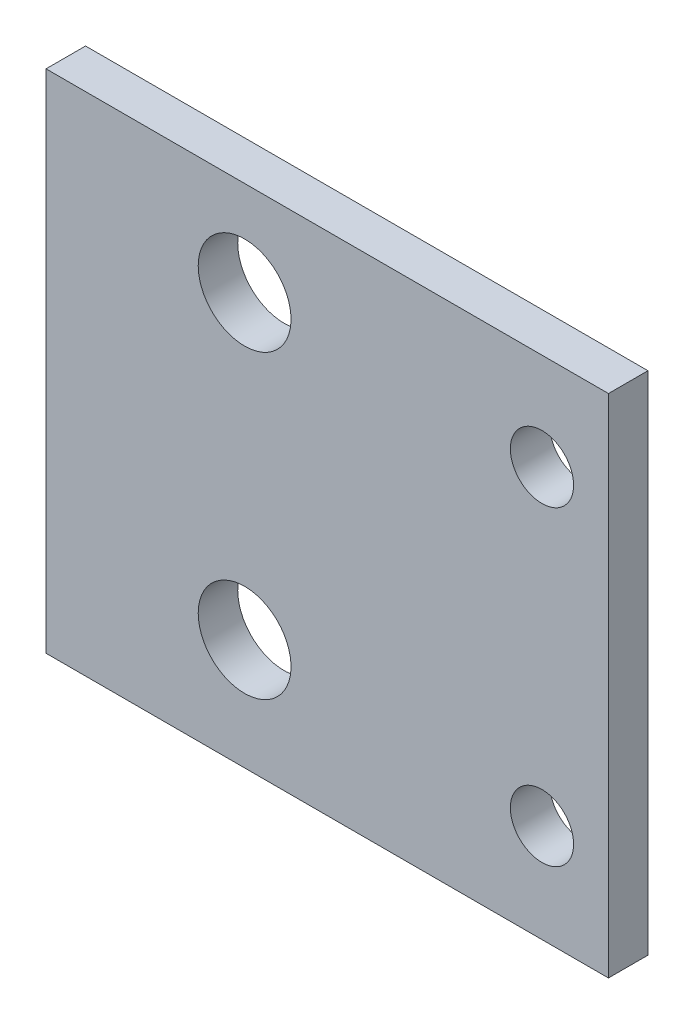
SolidWorks part; units mm, degrees
ref_plane "Front Plane" through (0, 0, 0) normal (0, 0, 1) x (1, 0, 0)
ref_plane "Top Plane" through (0, 0, 0) normal (0, 1, 0) x (1, 0, 0)
ref_plane "Right Plane" through (0, 0, 0) normal (1, 0, 0) x (0, 0, -1)
sketch "Sketch1" plane through (0, 0, 0) normal (0, 0, 1) x (1, 0, 0)
  line L1 (-20, -18) -> (20, -18)
  line L2 (-20, -18) -> (-20, 18)
  line L3 (-20, 18) -> (20, 18)
  line L4 (20, -18) -> (20, 18)
  line L5 (-20, -18) -> (20, 18) construction
  line L6 (-20, 18) -> (20, -18) construction
  point P0 (0, 0)
  dimension "D1" = 36
  dimension "D2" = 40
extrude "Boss-Extrude1" add sketch "Sketch1" along normal blind 2.81
hole_wizard "M4 Clearance Hole1" positions "Sketch3" profile "Sketch2" hole size "M4" standard "ANSI Metric" end condition through all
sketch "Sketch3" plane through (0, 0, 0) normal (0, 0, -1) x (-1, 0, 0)
  point P0 (-15.273, -11)
  point P3 (-15.273, 11.1109)
sketch "Sketch2" plane through (15.273, -11, 0) normal (1, 0, 0) x (0, 1, 0)
  line L0 (0, 0) -> (0, 2.81)
  line L1 (0, 2.81) -> (2.25, 2.81)
  line L2 (2.25, 2.81) -> (2.25, 0)
  line L5 (2.25, 0) -> (0, 0)
  line L11 (0, -6.35) -> (0, 107.95) construction
  dimension "Thru Hole Dia." = 4.5
  dimension "Thru Hole Depth" = 2.81
hole_wizard "M6 Clearance Hole1" positions "Sketch5" profile "Sketch4" hole size "M6" standard "ANSI Metric" end condition through all
sketch "Sketch5" plane through (0, 0, 0) normal (0, 0, -1) x (-1, 0, 0)
  point P0 (5.8771, -10.1116)
  point P2 (5.8771, 11.2827)
sketch "Sketch4" plane through (-5.8771, -10.1116, 0) normal (1, 0, 0) x (0, 1, 0)
  line L0 (0, 0) -> (0, 2.81)
  line L1 (0, 2.81) -> (3.3, 2.81)
  line L2 (3.3, 2.81) -> (3.3, 0)
  line L5 (3.3, 0) -> (0, 0)
  line L11 (0, -6.35) -> (0, 107.95) construction
  dimension "Thru Hole Dia." = 6.6
  dimension "Thru Hole Depth" = 2.81
